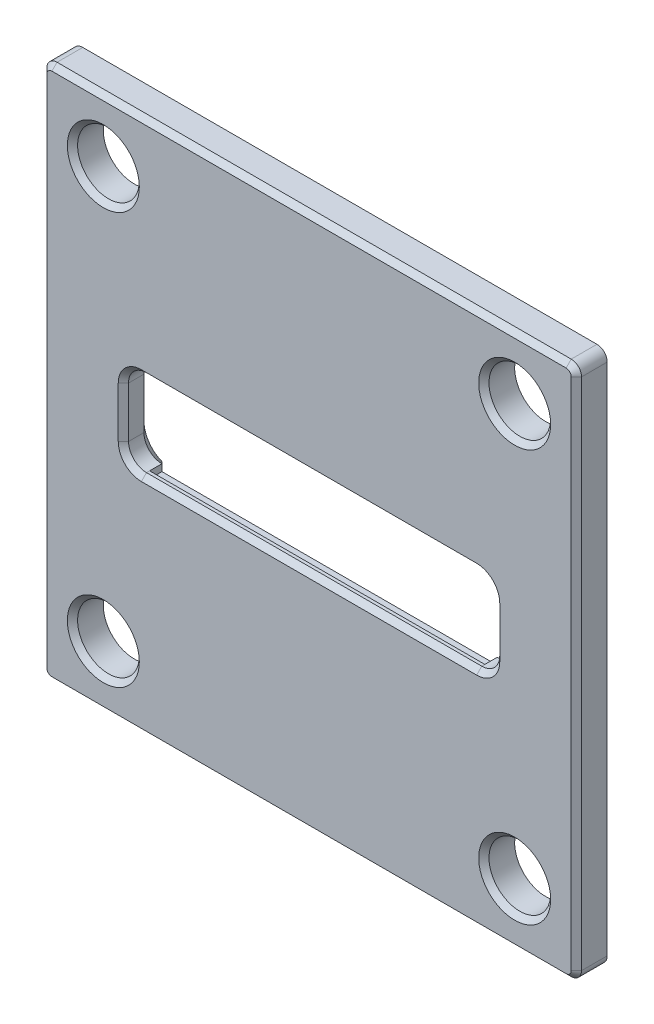
SolidWorks part; units mm, degrees
ref_plane "Front Plane" through (0, 0, 0) normal (1, 0, 0) x (0, 1, 0)
ref_plane "Top Plane" through (0, 0, 0) normal (0, 0, 1) x (0, 1, 0)
ref_plane "Right Plane" through (0, 0, 0) normal (0, 1, 0) x (-1, 0, 0)
sketch "Sketch1" plane through (0, 0, 0) normal (0, 0, 1) x (0, 1, 0)
  line L5 (-26.5, 25) -> (-26.5, 6.375) construction
  line L9 (26.5, -25) -> (26.5, -6.375) construction
  line L12 (-26.5, 26.5) -> (26.5, -26.5) construction
  line L13 (26.5, 26.5) -> (-26.5, -26.5) construction
  line L14 (25, -26.5) -> (-25, -26.5) construction
  line L15 (-25, 26.5) -> (25, 26.5) construction
  line L16 (0, 0) -> (0, 57.061) construction
  line L17 (0, 0) -> (0, -57.061) construction
  line L18 (0, 0) -> (0, 18.05) construction
  line L19 (0, 0) -> (-23, 0) construction
  line L21 (-26.5, 6.375) -> (-19.5, 6.375) construction
  line L22 (-26.5, 6.375) -> (-26.5, -6.375) construction
  line L23 (-26.5, -6.375) -> (-19.5, -6.375) construction
  line L24 (-19.5, 6.375) -> (-19.5, -6.375) construction
  line L25 (-26.5, 6.375) -> (-19.5, -6.375) construction
  line L26 (-26.5, -6.375) -> (-19.5, 6.375) construction
  line L28 (26.5, -6.375) -> (19.5, 6.375) construction
  line L35 (-2.46, 18.05) -> (2.46, 18.05)
  line L36 (4.21, 16.3) -> (4.21, -16.3)
  line L37 (2.46, -18.05) -> (-2.46, -18.05)
  line L38 (-4.21, 16.3) -> (-4.21, -16.3)
  line L39 (26.5, 6.375) -> (19.5, -6.375) construction
  line L40 (19.5, 6.375) -> (19.5, -6.375) construction
  line L41 (26.5, -6.375) -> (19.5, -6.375) construction
  line L42 (26.5, 6.375) -> (26.5, -6.375) construction
  line L43 (26.5, 6.375) -> (19.5, 6.375) construction
  line L46 (26.5, -6.375) -> (26.5, 6.375) construction
  line L47 (26.5, 6.375) -> (26.5, 25) construction
  line L50 (-26.5, 6.375) -> (-26.5, -6.375) construction
  line L51 (-26.5, -6.375) -> (-26.5, -25) construction
  line L52 (-25, 26) -> (25, 26)
  line L53 (26, 6.375) -> (26, 25)
  line L54 (26, 6.375) -> (26, -6.375)
  line L55 (26, -25) -> (26, -6.375)
  line L56 (25, -26) -> (-25, -26)
  line L57 (-26, -6.375) -> (-26, -25)
  line L58 (-26, 6.375) -> (-26, -6.375)
  line L59 (-26, 25) -> (-26, 6.375)
  circle A0 centre (-20, 20) radius 3
  circle A1 centre (20, 20) radius 3
  circle A2 centre (20, -20) radius 3
  circle A3 centre (-20, -20) radius 3
  arc A4 (-4.21, -16.3) -> (-2.46, -18.05) centre (-2.46, -16.3) ccw
  arc A5 (2.46, -18.05) -> (4.21, -16.3) centre (2.46, -16.3) ccw
  arc A6 (4.21, 16.3) -> (2.46, 18.05) centre (2.46, 16.3) ccw
  arc A7 (-2.46, 18.05) -> (-4.21, 16.3) centre (-2.46, 16.3) ccw
  arc A8 (-26.5, -25) -> (-25, -26.5) centre (-25, -25) ccw construction
  arc A9 (25, -26.5) -> (26.5, -25) centre (25, -25) ccw construction
  arc A10 (25, 26.5) -> (26.5, 25) centre (25, 25) cw construction
  arc A11 (-25, 26.5) -> (-26.5, 25) centre (-25, 25) ccw construction
  arc A12 (25, 26) -> (26, 25) centre (25, 25) cw
  arc A13 (25, -26) -> (26, -25) centre (25, -25) ccw
  arc A14 (-26, -25) -> (-25, -26) centre (-25, -25) ccw
  arc A15 (-25, 26) -> (-26, 25) centre (-25, 25) ccw
  point P23 (0, 0)
  point P32 (-4.21, 0)
  dimension "D6" = 6
  dimension "D13" = 1.75
  dimension "D3" = 1.5
  dimension "D2" = 53
  dimension "D4" = 0.5
  dimension "D5" = 6.5
  dimension "D8" = 7
  dimension "D9" = 12.75
  dimension "D10" = 23
  dimension "D11" = 8.42
  dimension "D12" = 36.1
  dimension "D7" = 4
extrude "Boss-Extrude1" add sketch "Sketch1" along normal blind 3
sketch "Sketch2" plane through (0, 0, 0) normal (0, 0, -1) x (1, 0, 0)
  line L1 (-16.3, 4.875) -> (16.3, 4.875)
  line L2 (-16.3, 4.875) -> (-16.3, -4.875)
  line L3 (-16.3, -4.875) -> (16.3, -4.875)
  line L4 (16.3, 4.875) -> (16.3, -4.875)
  line L5 (-16.3, 4.875) -> (16.3, -4.875) construction
  line L6 (-16.3, -4.875) -> (16.3, 4.875) construction
  point P0 (0, 0)
  point P6 (0, 0)
  dimension "D1" = 9.75
extrude "Cut-Extrude1" cut sketch "Sketch2" against normal blind 2.2
chamfer "Chamfer1" distance 1 angle 45 12 edges at (-17.5374, 3.6974, 0) (-17.5374, -3.6974, 0) (-18.05, 0, 0) (-16.3, 4.5425, 0) (0, 4.875, 0) (16.3, 4.5425, 0) (17.5374, 3.6974, 0) (18.05, 0, 0) (-16.3, -4.5425, 0) (17.5374, -3.6974, 0) (16.3, -4.5425, 0) (0, -4.875, 0)
chamfer "Chamfer3" distance 0.5 angle 45 20 edges at (17.5374, 3.6974, 3) (0, 4.21, 3) (-17.5374, 3.6974, 3) (-18.05, 0, 3) (-17.5374, -3.6974, 3) (0, -4.21, 3) (17.5374, -3.6974, 3) (18.05, 0, 3) (23, -20, 3) (-17, 20, 3) (-26, 0, 3) (-25.7071, 25.7071, 3) (0, 26, 3) (25.7071, 25.7071, 3) (26, 0, 3) (25.7071, -25.7071, 3) (0, -26, 3) (-25.7071, -25.7071, 3) (-17, -20, 3) (23, 20, 3)
